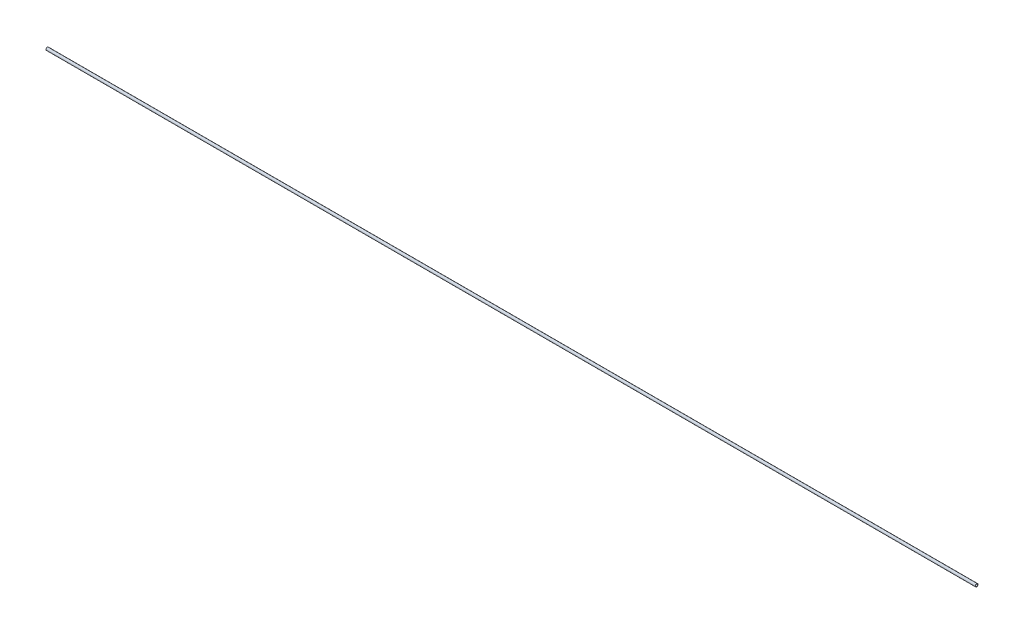
SolidWorks part; units mm, degrees
material "AISI 4130 Steel, annealed at 865C"
ref_plane "Front Plane" through (0, 0, 0) normal (0, 0, 1) x (1, 0, 0)
ref_plane "Top Plane" through (0, 0, 0) normal (0, 1, 0) x (1, 0, 0)
ref_plane "Right Plane" through (0, 0, 0) normal (1, 0, 0) x (0, 0, -1)
sketch "Sketch1" plane through (0, 0, 0) normal (1, 0, 0) x (0, 0, -1)
  circle A0 centre (0, 0) radius 12.7
  circle A1 centre (0, 0) radius 9.652
  dimension "D1" = 25.4
  dimension "D2" = 19.304
extrude "Boss-Extrude1" add sketch "Sketch1" along normal blind 8580
